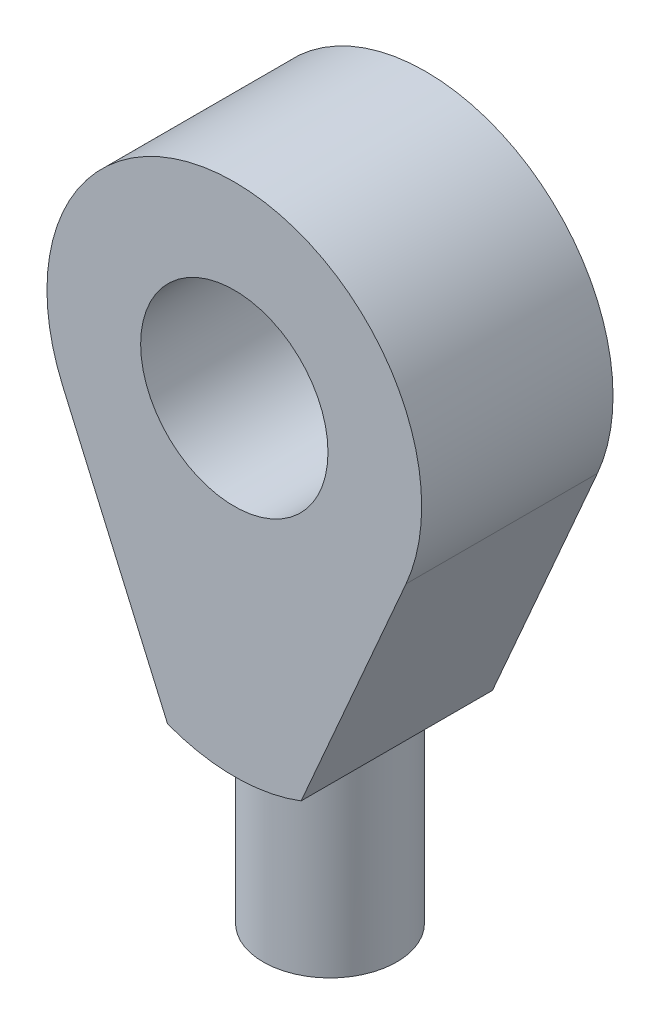
SolidWorks part; units mm, degrees
ref_plane "Front Plane" through (0, 0, 0) normal (0, 0, 1) x (1, 0, 0)
ref_plane "Top Plane" through (0, 0, 0) normal (0, 1, 0) x (1, 0, 0)
ref_plane "Right Plane" through (0, 0, 0) normal (1, 0, 0) x (0, 0, -1)
sketch "Sketch1" plane through (0, 0, 0) normal (0, 0, 1) x (1, 0, 0)
  line L0 (-4.5826, -2) -> (-1.7826, -8.4156)
  line L1 (4.5826, -2) -> (1.7826, -8.4156)
  circle A0 centre (0, 0) radius 2.5
  arc A1 (4.5826, -2) -> (-4.5826, -2) centre (0, 0) ccw
  arc A2 (-1.7826, -8.4156) -> (1.7826, -8.4156) centre (0, -3.7442) ccw
  dimension "D1" = 5
  dimension "D2" = 10
  dimension "D5" = 5
  dimension "D3" = 2
  dimension "D4" = 7
extrude "Boss-Extrude1" add sketch "Sketch1" along normal mid plane 5.107
sketch "Sketch2" plane through (0, 0, 0) normal (0, 0, 1) x (1, 0, 0)
  line L0 (0, -8.7442) -> (0, -12.1246) construction
  line L1 (1, -8.416) -> (1, -13.416)
  line L2 (1, -8.416) -> (1.783, -8.416)
  line L3 (1.783, -8.416) -> (1.783, -13.416)
  line L4 (1.783, -13.416) -> (1, -13.416)
  arc A0 (-1.7826, -8.4156) -> (1.7826, -8.4156) centre (0, -3.7442) ccw construction
  dimension "D1" = 1
  dimension "D2" = 5
  dimension "D3" = 0.783
  dimension "D4" = 8.416
revolve "Revolve1" add sketch "Sketch2" angle 360 about L0
